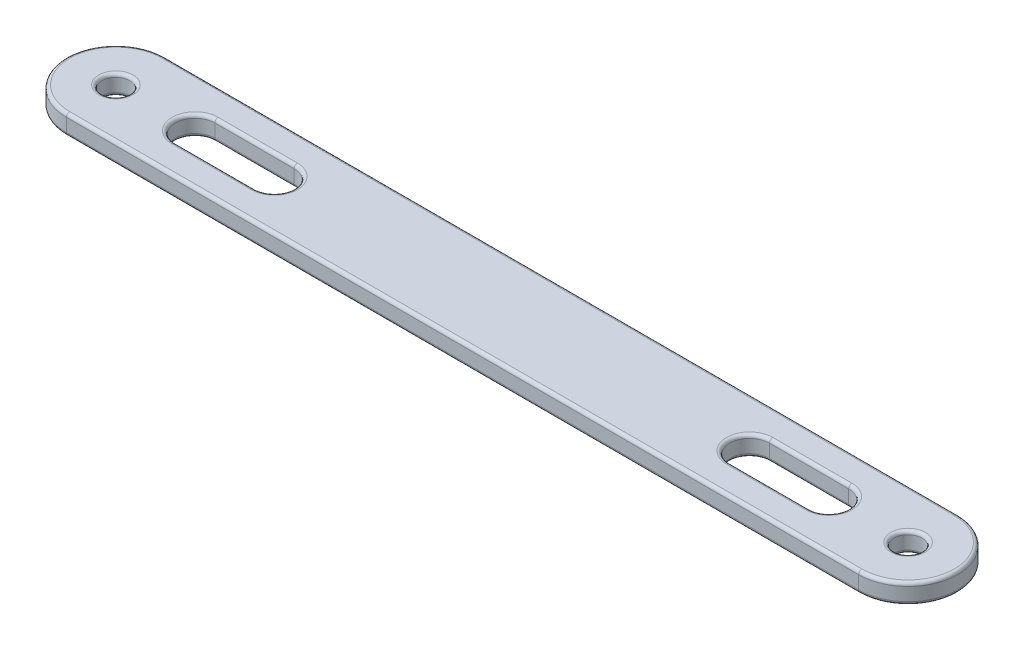
SolidWorks part; units mm, degrees
ref_plane "Front Plane" through (0, 0, 0) normal (0, 0, 1) x (1, 0, 0)
ref_plane "Top Plane" through (0, 0, 0) normal (0, 1, 0) x (1, 0, 0)
ref_plane "Right Plane" through (0, 0, 0) normal (1, 0, 0) x (0, 0, -1)
sketch "Sketch1" plane through (0, 0, 0) normal (0, 1, 0) x (1, 0, 0)
  line L0 (0, 7.5) -> (120, 7.5)
  line L1 (120, -7.5) -> (0, -7.5)
  circle A0 centre (0, 0) radius 2.1
  arc A1 (0, 7.5) -> (0, -7.5) centre (0, 0) ccw
  arc A2 (120, -7.5) -> (120, 7.5) centre (120, 0) ccw
  circle A3 centre (120, 0) radius 2.1
  dimension "D1" = 4.2
  dimension "D3" = 15
  dimension "D4" = 4.2
  dimension "D5" = 120
extrude "Boss-Extrude1" add sketch "Sketch1" along normal blind 3
sketch "Sketch3" plane through (0, 3, 0) normal (0, 1, 0) x (1, 0, 0)
  line L0 (60, 7.5) -> (60, 19.9379) construction
  line L1 (120, 7.5) -> (0, 7.5) construction
  line L2 (12, 0) -> (24, 0) construction
  line L3 (108, 0) -> (96, 0) construction
  line L4 (12, 3) -> (24, 3)
  line L5 (12, -3) -> (24, -3)
  line L6 (108, 3) -> (96, 3)
  line L7 (108, -3) -> (96, -3)
  arc A0 (12, 3) -> (12, -3) centre (12, 0) ccw
  arc A1 (24, -3) -> (24, 3) centre (24, 0) ccw
  arc A2 (108, 3) -> (108, -3) centre (108, 0) cw
  arc A3 (96, -3) -> (96, 3) centre (96, 0) cw
  point P9 (18, 0)
  point P14 (102, 0)
  dimension "D1" = 3
  dimension "D2" = 12
  dimension "D3" = 12
extrude "Cut-Extrude1" cut sketch "Sketch3" against normal through all
fillet "Fillet1" radius 0.5 28 edges at (93, 0, 0) (102, 0, -3) (111, 0, 0) (93, 3, 0) (102, 3, -3) (111, 3, 0) (127.5, 3, 0) (60, 3, 7.5) (-7.5, 3, 0) (127.5, 0, 0) (60, 0, 7.5) (-7.5, 0, 0) (18, 0, 3) (9, 0, 0) (18, 0, -3) (18, 3, 3) (9, 3, 0) (18, 3, -3) (120, 0, 2.1) (120, 3, 2.1) (102, 0, 3) (102, 3, 3) (60, 3, -7.5) (60, 0, -7.5) (0, 0, 2.1) (0, 3, 2.1) (27, 0, 0) (27, 3, 0)
